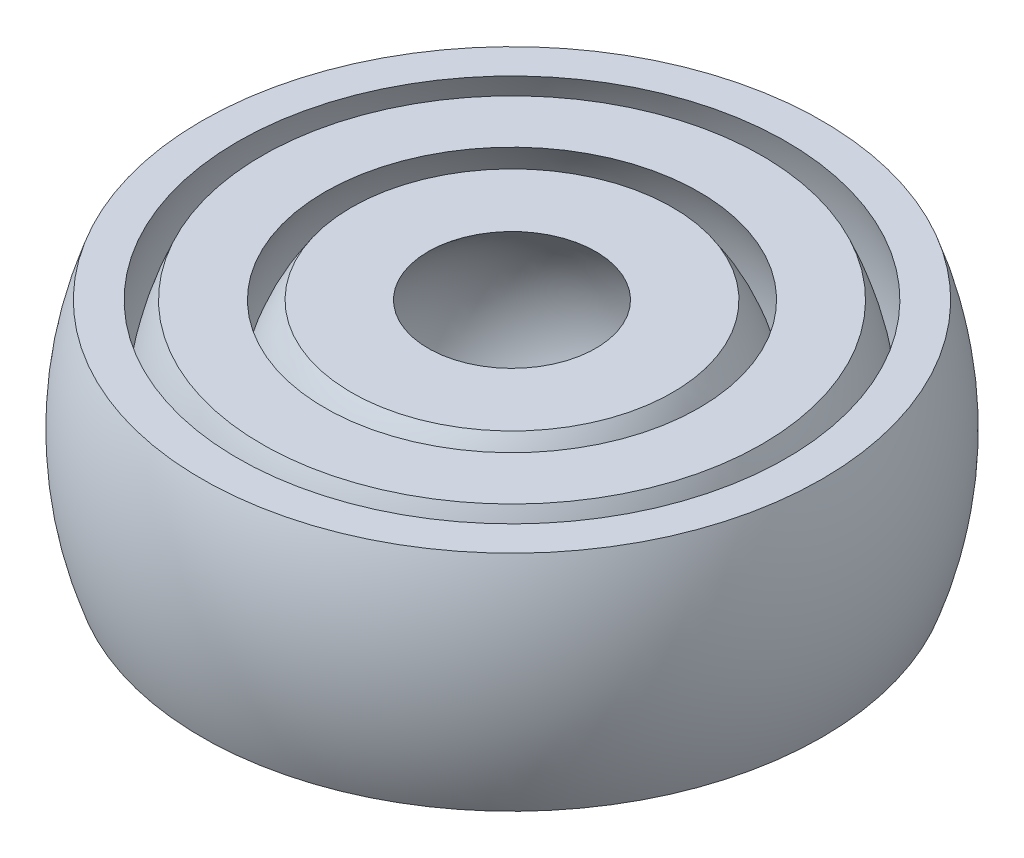
SolidWorks part; units mm, degrees
ref_plane "Alzado" through (0, 0, 0) normal (0, 0, 1) x (1, 0, 0)
ref_plane "Planta" through (0, 0, 0) normal (0, 1, 0) x (1, 0, 0)
ref_plane "Vista lateral" through (0, 0, 0) normal (1, 0, 0) x (0, 0, -1)
sketch "Croquis1" plane through (0, 0, 0) normal (0, 0, 1) x (1, 0, 0)
  line L0 (0, 12.7549) -> (0, -14.3107) construction
  line L1 (5.8858, -4) -> (0, -4) construction
  line L2 (-0.9954, 0) -> (1.8773, 0) construction
  line L3 (5.8858, 4) -> (0, 4) construction
  line L4 (0, -4) -> (-3, -4) construction
  line L5 (-3, -4) -> (-5.7446, -4)
  line L6 (0, 4) -> (-3, 4) construction
  line L7 (-3, 4) -> (-5.7446, 4)
  line L8 (-5.7446, 4) -> (-8.7584, 4) construction
  line L9 (-5.7446, -4) -> (-8.7584, -4) construction
  arc A0 (-3, 4) -> (-3, -4) centre (0, 0) ccw
  arc A1 (-5.7446, 4) -> (-5.7446, -4) centre (0, 0) ccw
  arc A2 (-5.7446, -4) -> (0, -7) centre (0, 0) ccw construction
  arc A3 (0, 7) -> (0, -7) centre (0, 0) ccw construction
  arc A4 (-3, -4) -> (0, -5) centre (0, 0) ccw construction
  arc A5 (0, 5) -> (0, -5) centre (0, 0) ccw construction
  arc A6 (0, 5) -> (-3, 4) centre (0, 0) ccw construction
  arc A7 (0, 7) -> (-5.7446, 4) centre (0, 0) ccw construction
  dimension "D1" = 10
  dimension "D3" = 4
  dimension "D2" = 2
revolve "Revolución1" add sketch "Croquis1" angle 360 about L0
sketch "Croquis3" plane through (0, 0, 0) normal (0, 0, 1) x (1, 0, 0)
  line L0 (6.6963, 4) -> (8.9465, 4)
  line L1 (6.6963, -4) -> (8.9465, -4)
  line L2 (8.9465, 4) -> (10.1817, 4) construction
  line L3 (5.7446, 4) -> (6.6963, 4) construction
  line L4 (8.9465, -4) -> (10.1817, -4) construction
  line L5 (5.7446, -4) -> (6.6963, -4) construction
  line L6 (0, 4.2236) -> (0, -5.2148) construction
  arc A1 (8.9465, -4) -> (8.9465, 4) centre (0, 0) ccw
  arc A2 (6.4011, -4.4571) -> (6.4011, 4.4571) centre (0, 0) ccw
  arc A3 (6.6963, -4) -> (6.6963, 4) centre (0, 0) ccw
  arc A4 (8.9465, 4) -> (8.0424, 5.6) centre (0, 0) ccw construction
  arc A5 (8.0424, -5.6) -> (8.0424, 5.6) centre (0, 0) ccw construction
  arc A6 (6.6963, 4) -> (6.4011, 4.4571) centre (0, 0) ccw construction
  arc A7 (6.4011, -4.4571) -> (6.4011, 4.4571) centre (0, 0) ccw construction
  arc A8 (8.0424, -5.6) -> (8.9465, -4) centre (0, 0) ccw construction
  arc A9 (6.4011, -4.4571) -> (6.6963, -4) centre (0, 0) ccw construction
  dimension "D1" = 0.8
  dimension "D2" = 2
revolve "Revolución2" add sketch "Croquis3" angle 360 about L6
sketch "Croquis4" plane through (0, 0, 0) normal (0, 0, 1) x (1, 0, 0)
  line L0 (-9.8163, 4) -> (-11.1014, 4)
  line L1 (-9.8163, -4) -> (-11.1014, -4)
  line L2 (-11.1014, 4) -> (-12.2361, 4) construction
  line L3 (-8.9465, 4) -> (-9.8163, 4) construction
  line L4 (-11.1014, -4) -> (-12.2361, -4) construction
  line L5 (-8.9465, -4) -> (-9.8163, -4) construction
  line L6 (0, 4.3265) -> (0, -4.8163) construction
  arc A2 (-10.7723, 4.8163) -> (-10.7723, -4.8163) centre (0, 0) ccw
  arc A3 (-11.1014, 4) -> (-11.1014, -4) centre (0, 0) ccw
  arc A4 (-10.7723, 4.8163) -> (-11.1014, 4) centre (0, 0) ccw construction
  arc A5 (-9.6768, 4.3265) -> (-9.6768, -4.3265) centre (0, 0) ccw
  arc A6 (-9.8163, 4) -> (-9.8163, -4) centre (0, 0) ccw
  arc A7 (-9.6768, 4.3265) -> (-9.8163, 4) centre (0, 0) ccw construction
  arc A8 (-9.8163, -4) -> (-9.6768, -4.3265) centre (0, 0) ccw construction
  arc A9 (-11.1014, -4) -> (-10.7723, -4.8163) centre (0, 0) ccw construction
  dimension "D1" = 2
  dimension "D2" = 0.8
revolve "Revolución3" add sketch "Croquis4" angle 360 about L6
